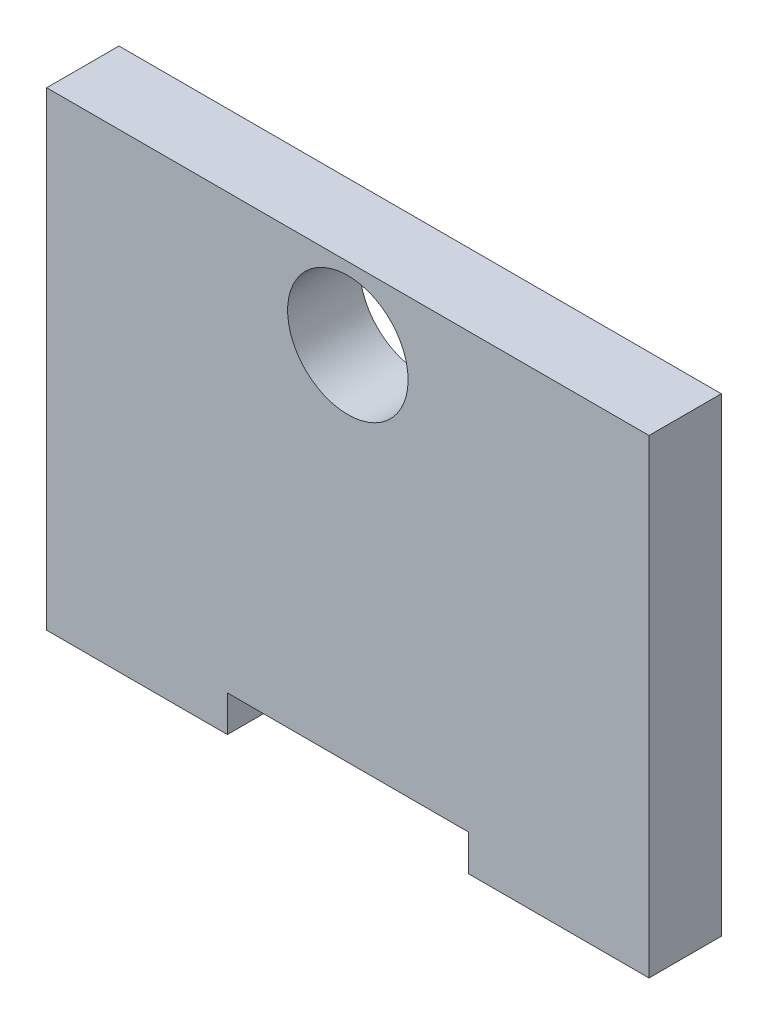
SolidWorks part; units mm, degrees
ref_plane "Plan de face" through (0, 0, 0) normal (0, 0, 1) x (1, 0, 0)
ref_plane "Plan de dessus" through (0, 0, 0) normal (0, 1, 0) x (1, 0, 0)
ref_plane "Plan de droite" through (0, 0, 0) normal (1, 0, 0) x (0, 0, -1)
sketch "Esquisse1" plane through (0, 0, 0) normal (0, 0, 1) x (1, 0, 0)
  line L0 (15, 0) -> (35, 0)
  line L1 (50, 0) -> (50, 36)
  line L2 (50, 36) -> (0, 36)
  line L3 (0, 36) -> (0, 0)
  line L4 (0, 18) -> (50, 18) construction
  line L12 (25, 42) -> (25, 18) construction
  line L14 (0, 0) -> (0, -3)
  line L15 (0, -3) -> (15, -3)
  line L16 (15, 0) -> (15, -3)
  line L18 (50, 0) -> (50, -3)
  line L19 (50, -3) -> (35, -3)
  line L20 (35, 0) -> (35, -3)
  circle A5 centre (25, 30) radius 5
  dimension "D5" = 3
  dimension "D6" = 3
  dimension "D3" = 10
  dimension "D1" = 36
  dimension "D2" = 50
  dimension "D4" = 30
  dimension "D7" = 15
  dimension "D8" = 15
  dimension "D9" = 3
extrude "Boss.-Extru.1" add sketch "Esquisse1" along normal blind 6
